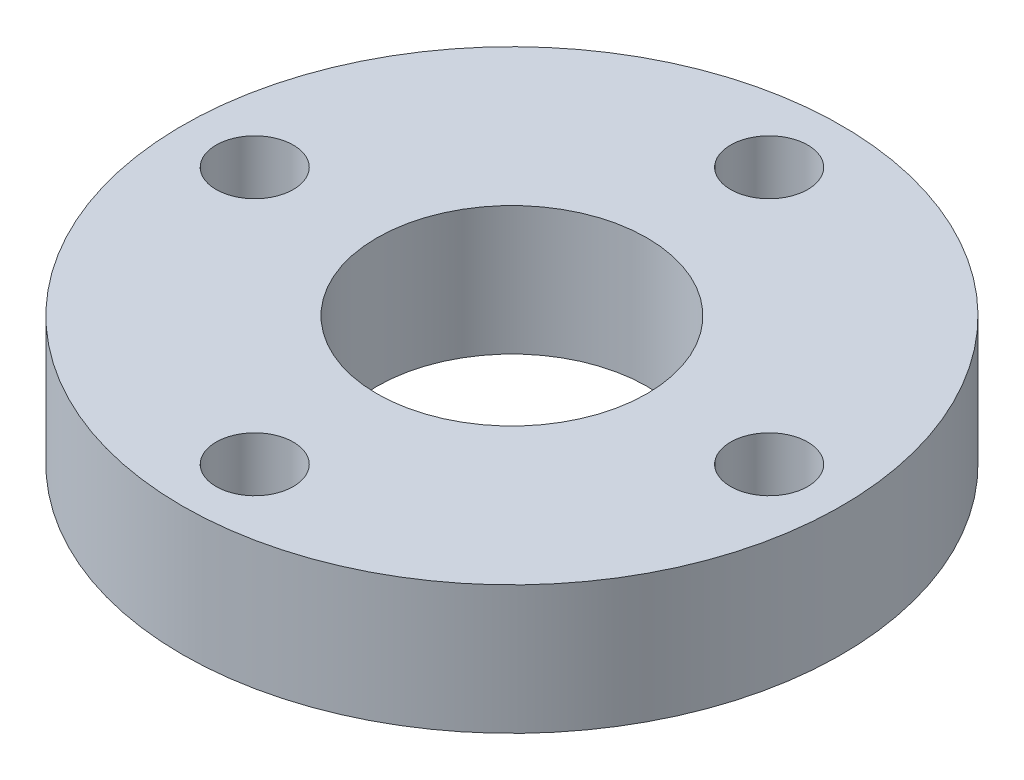
SolidWorks part; units mm, degrees
ref_plane "Front Plane" through (0, 0, 0) normal (0, 0, 1) x (1, 0, 0)
ref_plane "Top Plane" through (0, 0, 0) normal (0, 1, 0) x (1, 0, 0)
ref_plane "Right Plane" through (0, 0, 0) normal (1, 0, 0) x (0, 0, -1)
sketch "Sketch1" plane through (0, 0, 0) normal (0, 1, 0) x (1, 0, 0)
  circle A0 centre (0, 0) radius 10.25
  circle A1 centre (0, 0) radius 4.2
  circle A2 centre (0, 0) radius 8
  circle A3 centre (0, 8) radius 1.2
  circle A4 centre (8, 0) radius 1.2
  circle A5 centre (0, -8) radius 1.2
  circle A6 centre (-8, 0) radius 1.2
  point P16 (0, 0)
  dimension "D1" = 20.5
  dimension "D2" = 8.4
  dimension "D3" = 2.4
  dimension "D4" = 4
extrude "Boss-Extrude1" add sketch "Sketch1" along normal blind 4 contours A0 A6 A2 A3 A4 A5 | A6 A2 A5 A4 A3 A1
